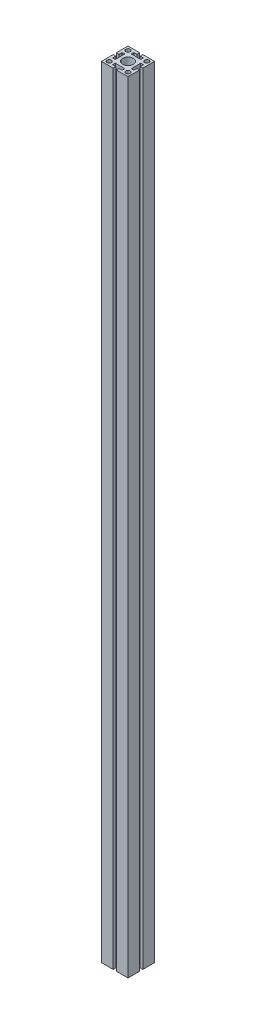
SolidWorks part; units mm, degrees
ref_plane "Front Plane" through (0, 0, 0) normal (0, 0, 1) x (1, 0, 0)
ref_plane "Top Plane" through (0, 0, 0) normal (0, 1, 0) x (1, 0, 0)
ref_plane "Right Plane" through (0, 0, 0) normal (1, 0, 0) x (0, 0, -1)
sketch "Sketch1" plane through (0, 0, 0) normal (0, 1, 0) x (1, 0, 0)
  line L1 (-25, -3) -> (-25, -25)
  line L6 (9, 20) -> (9, 15)
  line L7 (9, 20) -> (3, 20)
  line L8 (9, 15) -> (-9, 15)
  line L9 (3, 20) -> (3, 25)
  line L10 (-3, 25) -> (-25, 25)
  line L11 (-25, 25) -> (-25, 3)
  line L12 (-25, -25) -> (-3, -25)
  line L13 (25, -25) -> (25, -3)
  line L14 (3, 25) -> (25, 25)
  line L15 (-3, 20) -> (-3, 25)
  line L16 (-9, 20) -> (-9, 15)
  line L17 (3, -25) -> (25, -25)
  line L18 (25, 3) -> (25, 25)
  line L19 (-3, 20) -> (-9, 20)
  line L21 (-20, 9) -> (-15, 9)
  line L22 (-20, 9) -> (-20, 3)
  line L24 (-15, 9) -> (-15, -9)
  line L27 (-20, 3) -> (-25, 3)
  line L28 (20, -9) -> (15, -9)
  line L29 (20, -9) -> (20, -3)
  line L30 (15, -9) -> (15, 9)
  line L31 (20, -3) -> (25, -3)
  line L32 (20, 3) -> (25, 3)
  line L33 (-20, -3) -> (-25, -3)
  line L34 (20, 9) -> (15, 9)
  line L35 (20, 3) -> (20, 9)
  line L40 (-20, -9) -> (-15, -9)
  line L41 (-20, -3) -> (-20, -9)
  line L42 (-9, -20) -> (-9, -15)
  line L43 (-9, -20) -> (-3, -20)
  line L44 (-9, -15) -> (9, -15)
  line L45 (-3, -20) -> (-3, -25)
  line L46 (3, -20) -> (3, -25)
  line L47 (9, -20) -> (9, -15)
  line L48 (3, -20) -> (9, -20)
  circle A0 centre (0, 0) radius 10
  circle A1 centre (-17.6777, 17.6777) radius 4.1387
  circle A2 centre (17.6777, 17.6777) radius 4.1387
  circle A3 centre (17.6777, -17.6777) radius 4.1387
  circle A4 centre (-17.6777, -17.6777) radius 4.1387
  point P44 (0, 0)
  point P46 (0, 0)
  dimension "D1" = 4
extrude "Boss-Extrude1" add sketch "Sketch1" along normal blind 1470
